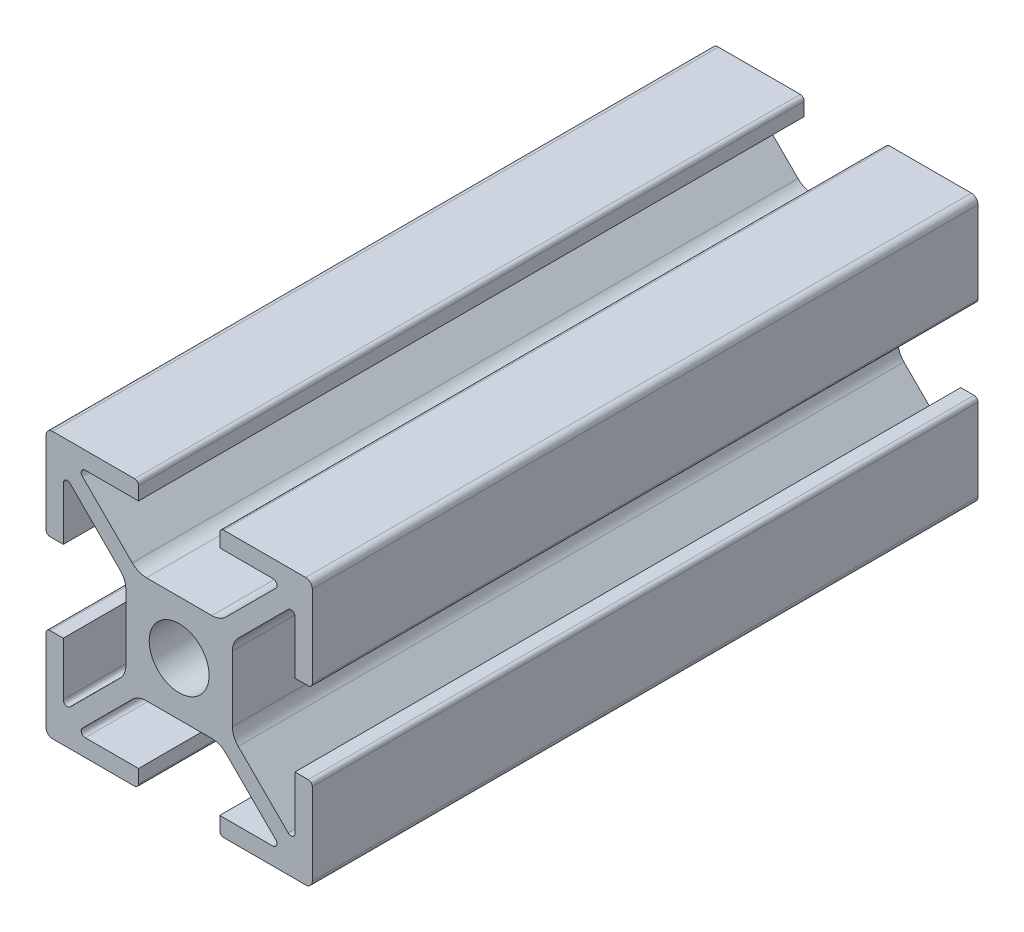
SolidWorks part; units mm, degrees
material "6063-T5"
ref_plane "Front" through (0, 0, 0) normal (0, 0, 1) x (1, 0, 0)
ref_plane "Top" through (0, 0, 0) normal (0, 1, 0) x (1, 0, 0)
ref_plane "Right" through (0, 0, 0) normal (1, 0, 0) x (0, 0, -1)
sketch "Esboço1" plane through (0, 0, 0) normal (1, 0, 0) x (0, 0, -1)
  line L0 (0, 0) -> (-50, 0)
  dimension "D1" = 50
other "Quadrado PF20-21 - PERFIL 2020 T-SLOT 6MM(1)"
ref_plane "Plano1" through (0, 0, 0) normal (0, 0, 1) x (0, -1, 0)
sketch "Esboço11" plane through (0, 0, 0) normal (0, 0, 1) x (0, -1, 0)
  line L0 (8.1879, -7.2686) -> (4.4393, -3.5201)
  line L1 (4, -2.4594) -> (4, 2.4594)
  line L2 (4.4393, 3.5201) -> (8.1879, 7.2686)
  line L3 (8.7, 7.0565) -> (8.7, 3.05)
  line L4 (10, 3.35) -> (10, 9.5)
  line L5 (9.5, 10) -> (3.35, 10)
  line L6 (3.05, 8.7) -> (7.0565, 8.7)
  line L7 (7.2686, 8.1879) -> (3.5201, 4.4393)
  line L8 (2.4594, 4) -> (-2.4594, 4)
  line L9 (-3.5201, 4.4393) -> (-7.2686, 8.1879)
  line L10 (-7.0565, 8.7) -> (-3.05, 8.7)
  line L11 (-3.35, 10) -> (-9.5, 10)
  line L12 (-10, 9.5) -> (-10, 3.35)
  line L13 (-8.7, 3.05) -> (-8.7, 7.0565)
  line L14 (-8.1879, 7.2686) -> (-4.4393, 3.5201)
  line L15 (-4, 2.4594) -> (-4, -2.4594)
  line L16 (-4.4393, -3.5201) -> (-8.1879, -7.2686)
  line L17 (-8.7, -7.0565) -> (-8.7, -3.05)
  line L18 (-10, -3.35) -> (-10, -9.5)
  line L19 (-9.5, -10) -> (-3.35, -10)
  line L20 (-3.05, -8.7) -> (-7.0565, -8.7)
  line L21 (-7.2686, -8.1879) -> (-3.5201, -4.4393)
  line L22 (-2.4594, -4) -> (2.4594, -4)
  line L23 (3.5201, -4.4393) -> (7.2686, -8.1879)
  line L24 (7.0565, -8.7) -> (3.05, -8.7)
  line L25 (3.05, -8.7) -> (3.05, -9.7)
  line L26 (3.35, -10) -> (9.5, -10)
  line L27 (10, -9.5) -> (10, -3.35)
  line L28 (8.7, -3.05) -> (9.7, -3.05)
  line L29 (8.7, -3.05) -> (8.7, -7.0565)
  line L30 (-3.05, 9.7) -> (-3.05, 8.7)
  line L31 (-9.7, -3.05) -> (-8.7, -3.05)
  line L32 (3.05, 9.7) -> (3.05, 8.7)
  line L33 (-9.7, 3.05) -> (-8.7, 3.05)
  line L34 (-3.05, -8.7) -> (-3.05, -9.7)
  line L35 (8.7, 3.05) -> (9.7, 3.05)
  circle A0 centre (0, 0) radius 2.25
  arc A1 (8.1879, -7.2686) -> (8.7, -7.0565) centre (8.4, -7.0565) ccw
  arc A2 (4, -2.4594) -> (4.4393, -3.5201) centre (5.5, -2.4594) ccw
  arc A3 (4.4393, 3.5201) -> (4, 2.4594) centre (5.5, 2.4594) ccw
  arc A4 (8.7, 7.0565) -> (8.1879, 7.2686) centre (8.4, 7.0565) ccw
  arc A5 (10, 9.5) -> (9.5, 10) centre (9.5, 9.5) ccw
  arc A6 (7.2686, 8.1879) -> (7.0565, 8.7) centre (7.0565, 8.4) ccw
  arc A7 (2.4594, 4) -> (3.5201, 4.4393) centre (2.4594, 5.5) ccw
  arc A8 (-3.5201, 4.4393) -> (-2.4594, 4) centre (-2.4594, 5.5) ccw
  arc A9 (-7.0565, 8.7) -> (-7.2686, 8.1879) centre (-7.0565, 8.4) ccw
  arc A10 (-9.5, 10) -> (-10, 9.5) centre (-9.5, 9.5) ccw
  arc A11 (-8.1879, 7.2686) -> (-8.7, 7.0565) centre (-8.4, 7.0565) ccw
  arc A12 (-4, 2.4594) -> (-4.4393, 3.5201) centre (-5.5, 2.4594) ccw
  arc A13 (-4.4393, -3.5201) -> (-4, -2.4594) centre (-5.5, -2.4594) ccw
  arc A14 (-8.7, -7.0565) -> (-8.1879, -7.2686) centre (-8.4, -7.0565) ccw
  arc A15 (-10, -9.5) -> (-9.5, -10) centre (-9.5, -9.5) ccw
  arc A16 (-7.2686, -8.1879) -> (-7.0565, -8.7) centre (-7.0565, -8.4) ccw
  arc A17 (-2.4594, -4) -> (-3.5201, -4.4393) centre (-2.4594, -5.5) ccw
  arc A18 (3.5201, -4.4393) -> (2.4594, -4) centre (2.4594, -5.5) ccw
  arc A19 (7.0565, -8.7) -> (7.2686, -8.1879) centre (7.0565, -8.4) ccw
  arc A20 (9.5, -10) -> (10, -9.5) centre (9.5, -9.5) ccw
  arc A21 (-9.7, 3.05) -> (-10, 3.35) centre (-9.7, 3.35) cw
  arc A22 (-9.7, -3.05) -> (-10, -3.35) centre (-9.7, -3.35) ccw
  arc A23 (-3.05, -9.7) -> (-3.35, -10) centre (-3.35, -9.7) cw
  arc A24 (3.05, -9.7) -> (3.35, -10) centre (3.35, -9.7) ccw
  arc A25 (9.7, -3.05) -> (10, -3.35) centre (9.7, -3.35) cw
  arc A26 (9.7, 3.05) -> (10, 3.35) centre (9.7, 3.35) ccw
  arc A27 (3.05, 9.7) -> (3.35, 10) centre (3.35, 9.7) cw
  arc A28 (-3.05, 9.7) -> (-3.35, 10) centre (-3.35, 9.7) ccw
  point P0 (0, 10)
  point P1 (-10, 10)
  point P2 (0, 0)
  point P3 (10, 10)
  point P4 (10, 0)
  point P5 (10, -10)
  point P6 (0, -10)
  point P7 (-10, -10)
  point P8 (-10, 0)
  point P9 (0, 0)
  point P88 (0, 0)
